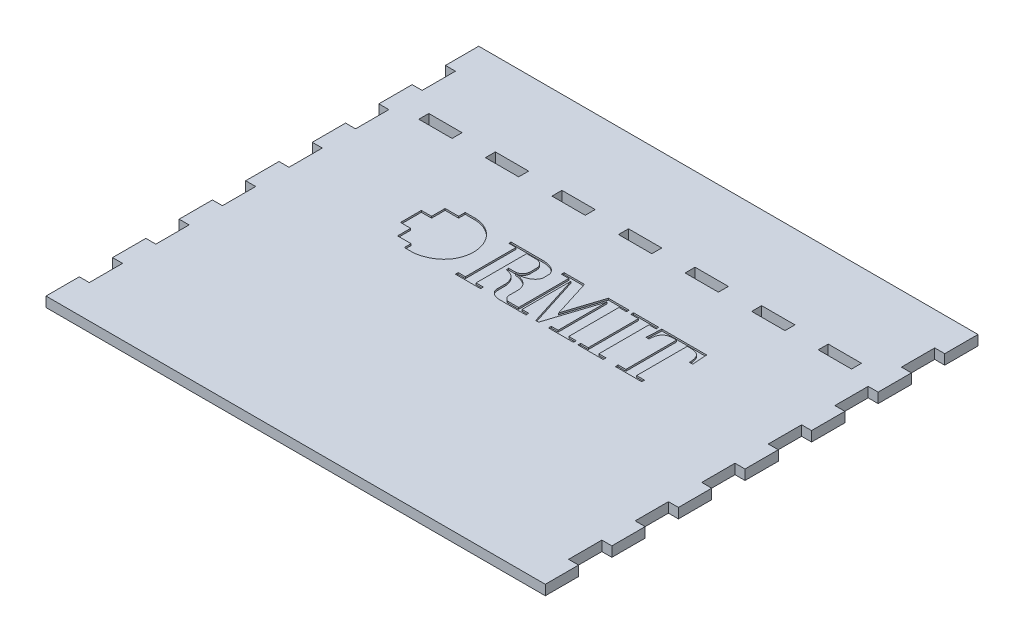
SolidWorks part; units mm, degrees
material "Oak"
ref_plane "Front Plane" through (0, 0, 0) normal (0, 0, 1) x (1, 0, 0)
ref_plane "Top Plane" through (0, 0, 0) normal (0, 1, 0) x (1, 0, 0)
ref_plane "Right Plane" through (0, 0, 0) normal (1, 0, 0) x (0, 0, -1)
sketch "Sketch1" plane through (0, 0, 0) normal (0, 1, 0) x (1, 0, 0)
  line L1 (-75, -65) -> (75, -65)
  line L2 (-75, -65) -> (-75, 65)
  line L3 (-75, 65) -> (75, 65)
  line L4 (75, -65) -> (75, 65)
  line L5 (-75, -65) -> (75, 65) construction
  line L6 (-75, 65) -> (75, -65) construction
  point P0 (0, 0)
  dimension "D1" = 150
  dimension "D2" = 130
extrude "Boss-Extrude1" add sketch "Sketch1" along normal blind 3
sketch "Sketch3" plane through (0, 3, 0) normal (0, 1, 0) x (1, 0, 0)
  line L0 (75, -65) -> (75, 65) construction
  line L1 (75, -55) -> (72, -55)
  line L2 (75, -55) -> (75, -45)
  line L3 (75, -45) -> (72, -45)
  line L4 (72, -55) -> (72, -45)
  line L5 (-75, -65) -> (75, -65) construction
  dimension "D1" = 10
  dimension "D2" = 3
  dimension "D3" = 10
extrude "Cut-Extrude1" cut sketch "Sketch3" against normal through all
pattern_linear "LPattern1" count 6 spacing 20 along (0, 0, -1) of "Cut-Extrude1"
mirror "Mirror1" about plane through (0, 0, 0) normal (1, 0, 0) of "LPattern1", "Cut-Extrude1"
sketch "Sketch4" plane through (0, 0, 0) normal (0, -1, 0) x (1, 0, 0)
  line L0 (75, -65) -> (-75, -65) construction
  line L1 (65, -40) -> (55, -40)
  line L2 (65, -40) -> (65, -37)
  line L3 (65, -37) -> (55, -37)
  line L4 (55, -40) -> (55, -37)
  line L5 (75, -35) -> (75, -45) construction
  dimension "D1" = 10
  dimension "D2" = 3
  dimension "D3" = 25
  dimension "D4" = 10
extrude "Cut-Extrude2" cut sketch "Sketch4" against normal through all
pattern_linear "LPattern2" count 7 spacing 20 along (-1, 0, 0) of "Cut-Extrude2"
sketch "Sketch7" plane through (0, 3, 0) normal (0, 1, 0) x (1, 0, 0)
  line L0 (-30.6629, 19.7219) -> (-33.7813, 19.7219)
  line L1 (-33.7813, 19.7219) -> (-33.7813, 17.7402)
  line L2 (-33.7813, 17.7402) -> (-37.8323, 17.7402)
  line L3 (-37.8323, 17.7402) -> (-37.8323, 13.66)
  line L4 (-37.8323, 13.66) -> (-40.8923, 13.66)
  line L5 (-40.8923, 13.66) -> (-40.8923, 7.3941)
  line L6 (-40.8923, 7.3941) -> (-37.8323, 7.3941)
  line L7 (-37.8323, 7.3941) -> (-37.8323, 3.4597)
  line L8 (-37.8323, 3.4597) -> (-33.7813, 3.4597)
  line L9 (-33.7813, 3.4597) -> (-33.7813, 1.4488)
  line L10 (-33.7813, 1.4488) -> (-30.6629, 1.4488)
  line L11 (-9.8251, 18.9059) -> (-19.1803, 18.9059)
  line L12 (-19.1803, 18.9059) -> (-19.1803, 18.2356)
  line L13 (-19.1803, 18.2356) -> (-17.0236, 18.2356)
  line L14 (-17.0236, 18.2356) -> (-17.0236, 3.0226)
  line L15 (-17.0236, 3.0226) -> (-19.1803, 3.0226)
  line L16 (-19.1803, 3.0226) -> (-19.1803, 2.1774)
  line L17 (-19.1803, 2.1774) -> (-11.632, 2.1774)
  line L18 (-11.632, 2.1774) -> (-11.632, 3.0226)
  line L19 (-11.632, 3.0226) -> (-13.8178, 3.0226)
  line L20 (-13.8178, 3.0226) -> (-13.8178, 11.008)
  line L21 (-12.7249, 11.008) -> (-12.7249, 11.7366)
  line L22 (-12.7249, 11.7366) -> (-10.7577, 11.7366)
  line L23 (-13.8178, 11.7366) -> (-13.8178, 18.2356)
  line L24 (-13.8178, 18.2356) -> (-10.7577, 18.2356)
  line L25 (-8.5515, 15.8662) -> (-8.5515, 13.8315)
  line L26 (-5.0353, 15.96) -> (-5.0353, 14.3847)
  line L27 (-9.117, 7.1607) -> (-9.117, 4.837)
  line L28 (-5.6136, 4.6403) -> (-5.6136, 7.1607)
  line L29 (-4.1121, 3.0226) -> (-1.0377, 3.0226)
  line L30 (-1.0377, 3.0226) -> (-1.0377, 18.0901)
  line L31 (-1.0377, 18.0901) -> (-3.2644, 18.0901)
  line L32 (-3.2644, 18.0901) -> (-3.2644, 18.9059)
  line L33 (-3.2644, 18.9059) -> (2.8578, 18.9059)
  line L34 (2.8578, 18.9059) -> (6.4027, 7.6363)
  line L35 (6.4027, 7.6363) -> (10.0459, 18.9059)
  line L36 (10.0459, 18.9059) -> (16.2803, 18.9059)
  line L37 (16.2803, 18.9059) -> (16.2803, 18.0901)
  line L38 (16.2803, 18.0901) -> (14.0398, 18.0901)
  line L39 (14.0398, 18.0901) -> (14.0398, 3.0226)
  line L40 (14.0398, 3.0226) -> (16.2803, 3.0226)
  line L41 (16.2803, 3.0226) -> (16.2803, 2.1774)
  line L42 (16.2803, 2.1774) -> (8.7795, 2.1774)
  line L43 (8.7795, 2.1774) -> (8.7795, 3.0226)
  line L44 (8.7795, 3.0226) -> (10.8252, 3.0226)
  line L45 (10.8252, 3.0226) -> (10.8252, 17.7402)
  line L46 (10.8252, 17.7402) -> (5.7941, 2.1774)
  line L47 (5.7941, 2.1774) -> (4.9415, 2.1774)
  line L48 (4.9415, 2.1774) -> (0, 17.7402)
  line L49 (0, 17.7402) -> (0, 3.0226)
  line L50 (0, 3.0226) -> (2.0191, 3.0226)
  line L51 (2.0191, 3.0226) -> (2.0191, 2.1774)
  line L52 (2.0191, 2.1774) -> (-5.4231, 2.1774)
  line L53 (17.6142, 18.9059) -> (25.1993, 18.9059)
  line L54 (25.1993, 18.9059) -> (25.1993, 18.0901)
  line L55 (25.1993, 18.0901) -> (23.0807, 18.0901)
  line L56 (23.0807, 18.0901) -> (23.0807, 3.0226)
  line L57 (23.0807, 3.0226) -> (25.1993, 3.0226)
  line L58 (25.1993, 3.0226) -> (25.1993, 2.1774)
  line L59 (25.1993, 2.1774) -> (17.6142, 2.1774)
  line L60 (17.6142, 2.1774) -> (17.6142, 3.0226)
  line L61 (17.6142, 3.0226) -> (19.8897, 3.0226)
  line L62 (19.8897, 3.0226) -> (19.8897, 18.0901)
  line L63 (19.8897, 18.0901) -> (17.6142, 18.0901)
  line L64 (17.6142, 18.0901) -> (17.6142, 18.9059)
  line L65 (25.8793, 14.3847) -> (26.1147, 18.9059)
  line L66 (26.1147, 18.9059) -> (39.5848, 18.9059)
  line L67 (39.5848, 18.9059) -> (39.8725, 14.3847)
  line L68 (39.8725, 14.3847) -> (38.9047, 14.3847)
  line L69 (25.8793, 14.3847) -> (26.7425, 14.3847)
  line L70 (28.8872, 3.0226) -> (28.8872, 2.1774)
  line L71 (28.8872, 2.1774) -> (36.7862, 2.1774)
  line L72 (36.7862, 2.1774) -> (36.7862, 3.0226)
  line L73 (36.7862, 3.0226) -> (34.4118, 3.0226)
  line L74 (34.4118, 3.0226) -> (34.4118, 18.2356)
  line L75 (28.8872, 3.0226) -> (31.1889, 3.0226)
  line L76 (31.1889, 3.0226) -> (31.1889, 18.2356)
  line L77 (-13.8178, 11.7366) -> (-13.8178, 11.008)
  spline S0 degree 3 poles (-30.6629, 19.7219) (-20.3533, 19.1026) (-18.3863, 3.7074) (-30.6629, 1.4488) knots 0 0 0 0 1 1 1 1
  spline S1 degree 3 poles (-10.7577, 18.2356) (-9.2776, 18.0635) (-8.575, 17.0618) (-8.5515, 15.8662) knots 0 0 0 0 1 1 1 1
  spline S2 degree 3 poles (-10.7577, 11.7366) (-9.4182, 11.9173) (-8.7039, 12.7297) (-8.5515, 13.8315) knots 0 0 0 0 1 1 1 1
  spline S3 degree 3 poles (-9.8251, 18.9059) (-6.9572, 18.9555) (-5.0502, 17.6484) (-5.0353, 15.96) knots 0 0 0 0 1 1 1 1
  spline S4 degree 3 poles (-5.0353, 14.3847) (-5.2307, 12.6838) (-7.5823, 11.276) (-10.3506, 11.3964) knots 0 0 0 0 1 1 1 1
  spline S5 degree 3 poles (-12.7249, 11.008) (-10.6063, 10.8166) (-9.256, 9.4566) (-9.117, 7.1607) knots 0 0 0 0 1 1 1 1
  spline S6 degree 3 poles (-10.3506, 11.3964) (-7.0693, 11.0151) (-5.53, 9.5261) (-5.6136, 7.1607) knots 0 0 0 0 1 1 1 1
  spline S7 degree 3 poles (-5.6136, 4.6403) (-5.5546, 3.788) (-4.7824, 3.0391) (-4.1121, 3.0226) knots 0 0 0 0 1 1 1 1
  spline S8 degree 3 poles (-9.117, 4.837) (-9.1551, 3.3025) (-7.8277, 2.1052) (-5.4231, 2.1774) knots 0 0 0 0 1 1 1 1
  spline S9 degree 3 poles (31.1889, 18.2356) (27.5648, 18.5152) (26.8798, 16.9023) (26.7425, 14.3847) knots 0 0 0 0 1 1 1 1
  spline S10 degree 3 poles (34.4118, 18.2356) (38.2133, 18.4533) (38.8124, 16.9799) (38.9047, 14.3847) knots 0 0 0 0 1 1 1 1
extrude "Cut-Extrude3" cut sketch "Sketch7" against normal blind 0.5
